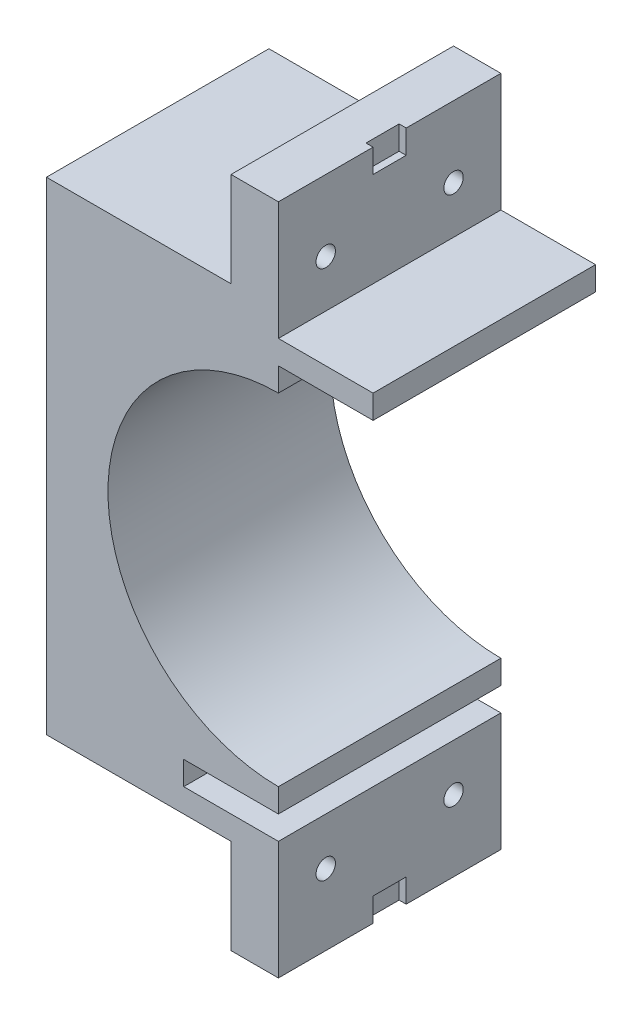
SolidWorks part; units mm, degrees
ref_plane "前视基准面" through (0, 0, 0) normal (0, 0, 1) x (1, 0, 0)
ref_plane "上视基准面" through (0, 0, 0) normal (0, 1, 0) x (1, 0, 0)
ref_plane "右视基准面" through (0, 0, 0) normal (1, 0, 0) x (0, 0, -1)
other "Configuration Table"
sketch "草图1" plane through (0, 0, 0) normal (0, 0, 1) x (1, 0, 0)
  line L1 (0, 36) -> (0, 51)
  line L2 (0, 51) -> (-49, 51)
  line L3 (-49, 51) -> (-49, -51)
  line L4 (-49, -51) -> (0, -51)
  line L5 (0, -51) -> (0, -36)
  arc A0 (0, 36) -> (0, -36) centre (0, 0) ccw
  dimension "D1" = 72
  dimension "D2" = 15
  dimension "10" = 15
  dimension "D3" = 49
extrude "凸台-拉伸1" add sketch "草图1" along normal blind 47
ref_plane "基准面1" through (-10, 0, 0) normal (1, 0, 0) x (0, 0, -1)
sketch "草图2" plane through (-10, 0, 0) normal (1, 0, 0) x (0, 0, -1)
  line L15 (-47, -51) -> (0, -51)
  line L16 (-47, -51) -> (-47, -71)
  line L17 (-47, -71) -> (0, -71)
  line L18 (0, -51) -> (0, -71)
  line L19 (-47, 51) -> (0, 51)
  line L20 (-47, 51) -> (-47, 71)
  line L21 (-47, 71) -> (0, 71)
  line L22 (0, 51) -> (0, 71)
  dimension "D1" = 20
  dimension "D2" = 20
extrude "凸台-拉伸2" add sketch "草图2" along normal blind 10
sketch "草图3" plane through (0, 0, 47) normal (0, 0, 1) x (1, 0, 0)
  line L0 (0, 36) -> (0, 71) construction
  line L1 (0, 46) -> (20, 46)
  line L2 (0, 46) -> (0, 41)
  line L3 (0, 41) -> (20, 41)
  line L4 (20, 46) -> (20, 41)
  line L5 (-10, 51) -> (-49, 51) construction
  dimension "D1" = 5
  dimension "D2" = 5
  dimension "D3" = 20
extrude "凸台-拉伸3" add sketch "草图3" against normal through all
sketch "草图4" plane through (0, 0, 47) normal (0, 0, 1) x (1, 0, 0)
  line L0 (0, -71) -> (0, -36) construction
  line L1 (0, -41) -> (-20, -41)
  line L2 (0, -41) -> (0, -46)
  line L3 (0, -46) -> (-20, -46)
  line L4 (-20, -41) -> (-20, -46)
  line L5 (-49, -51) -> (-10, -51) construction
  dimension "D1" = 5
  dimension "5" = 5
  dimension "D3" = 20
extrude "切除-拉伸1" cut sketch "草图4" against normal through all
sketch "草图5" plane through (-10, 0, 0) normal (-1, 0, 0) x (0, 0, 1)
  line L0 (47, -71) -> (0, -71) construction
  line L1 (0, -71) -> (0, -51) construction
  line L2 (47, -51) -> (47, -71) construction
  circle A0 centre (10, -56) radius 2.05
  circle A1 centre (37, -56) radius 2.05
  dimension "D3" = 4.1
  dimension "D4" = 4.1
  dimension "D1" = 15
  dimension "D2" = 15
  dimension "D5" = 10
  dimension "D6" = 10
extrude "切除-拉伸2" cut sketch "草图5" against normal blind 10
sketch "草图6" plane through (-10, 0, 0) normal (-1, 0, 0) x (0, 0, 1)
  line L0 (0, 71) -> (47, 71) construction
  line L1 (0, 51) -> (0, 71) construction
  line L2 (47, 71) -> (47, 51) construction
  circle A0 centre (10, 56) radius 2.05
  circle A1 centre (37, 56) radius 2.05
  dimension "D3" = 4.1
  dimension "D4" = 4.1
  dimension "D1" = 15
  dimension "D2" = 15
  dimension "D5" = 10
  dimension "D6" = 10
extrude "切除-拉伸3" cut sketch "草图6" against normal blind 10
ref_plane "基准面2" through (0, 0, 2) normal (0, 0, 1) x (1, 0, 0)
sketch "草图7" plane through (0, -71, 0) normal (0, -1, 0) x (1, 0, 0)
  line L0 (0, 47) -> (0, 0) construction
  line L1 (0, 27) -> (-1.5, 27)
  line L2 (0, 27) -> (0, 20)
  line L3 (0, 20) -> (-1.5, 20)
  line L4 (-1.5, 27) -> (-1.5, 20)
  line L5 (0, 47) -> (-10, 47) construction
  line L6 (0, 0) -> (-10, 0) construction
  dimension "D1" = 20
  dimension "D2" = 20
  dimension "D3" = 1.5
extrude "切除-拉伸4" cut sketch "草图7" against normal blind 5
sketch "草图8" plane through (0, 71, 0) normal (0, 1, 0) x (1, 0, 0)
  line L4 (-1.5, -27) -> (0, -27)
  line L5 (-1.5, -20) -> (-1.5, -27)
  line L6 (0, -20) -> (-1.5, -20)
  line L7 (0, -27) -> (0, -20)
  line L8 (-1.5, -27) -> (0, -27)
  line L9 (-1.5, -20) -> (-1.5, -27)
  line L10 (0, -20) -> (-1.5, -20)
  line L11 (0, -27) -> (0, -20)
  dimension "D1" = 0
extrude "切除-拉伸5" cut sketch "草图8" against normal blind 5
sketch "草图9" plane through (-49, 0, 0) normal (-1, 0, 0) x (0, 0, 1)
  line L0 (0, 51) -> (0, -51) construction
  line L1 (0, -3.5) -> (1.8, -3.5)
  line L2 (0, -3.5) -> (0, 3.5)
  line L3 (0, 3.5) -> (1.8, 3.5)
  line L4 (1.8, -3.5) -> (1.8, 3.5)
  line L5 (47, 51) -> (0, 51) construction
  dimension "D1" = 1.8
  dimension "D2" = 47.5
  dimension "D3" = 7
extrude "切除-拉伸6" cut sketch "草图9" against normal blind 6
